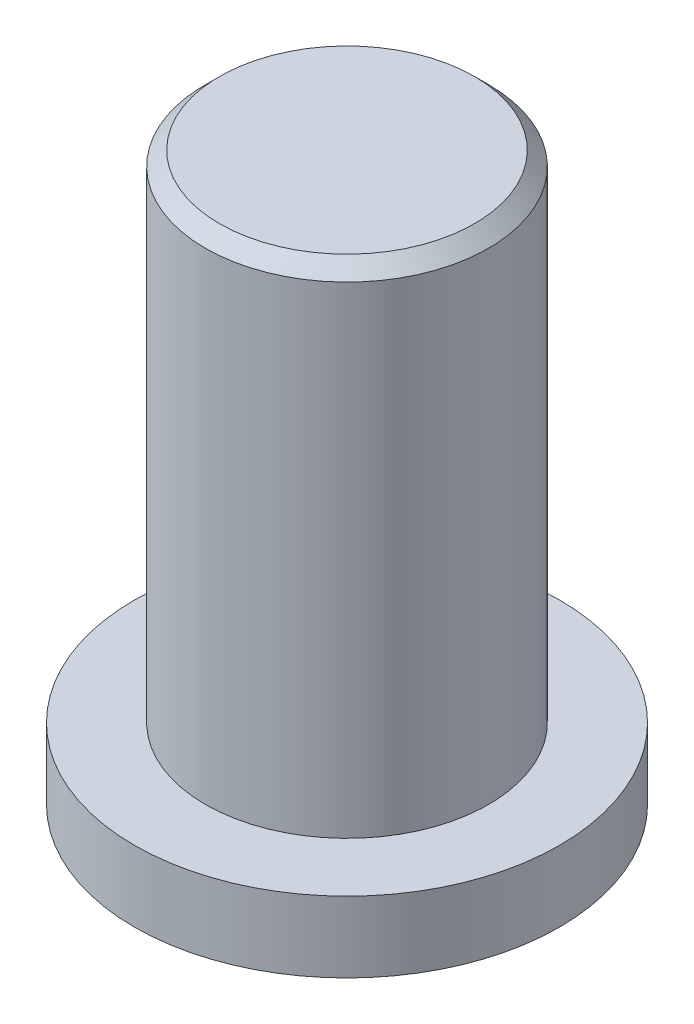
SolidWorks part; units mm, degrees
ref_plane "Front Plane" through (0, 0, 0) normal (0, 0, 1) x (1, 0, 0)
ref_plane "Top Plane" through (0, 0, 0) normal (0, 1, 0) x (1, 0, 0)
ref_plane "Right Plane" through (0, 0, 0) normal (1, 0, 0) x (0, 0, -1)
sketch "Sketch1" plane through (0, 0, 0) normal (0, 0, 1) x (1, 0, 0)
  line L0 (0, 28.7166) -> (0, -16.6845) construction
  line L1 (0, 0) -> (0, 40)
  line L2 (0, 40) -> (10, 40)
  line L3 (10, 40) -> (10, 5)
  line L4 (10, 5) -> (15, 5)
  line L5 (15, 5) -> (15, 0)
  line L6 (15, 0) -> (0, 0)
  dimension "D1" = 15
  dimension "D2" = 10
  dimension "D3" = 35
  dimension "D4" = 5
revolve "Revolve1" add sketch "Sketch1" angle 360 about L0
chamfer "Chamfer1" distance 1 angle 45 1 edges at (0, 40, 10)
